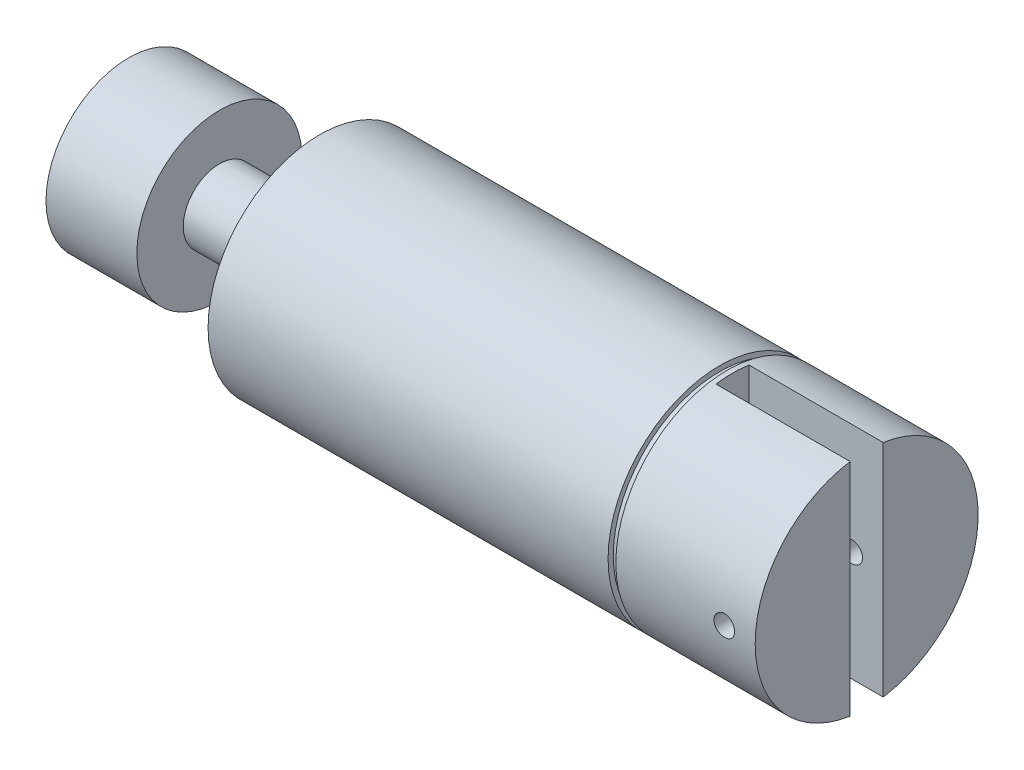
SolidWorks part; units mm, degrees
ref_plane "Front" through (0, 0, 0) normal (0, 0, 1) x (1, 0, 0)
ref_plane "Top" through (0, 0, 0) normal (0, 1, 0) x (1, 0, 0)
ref_plane "Right" through (0, 0, 0) normal (1, 0, 0) x (0, 0, -1)
sketch "Sketch1" plane through (0, 0, 0) normal (0, 0, 1) x (1, 0, 0)
  line L0 (-38.3901, 0) -> (38.3901, 0) construction
  line L1 (-57.25, 0) -> (-57.25, 8)
  line L2 (-57.25, 8) -> (-57.0422, 8)
  line L3 (-57.0422, 8) -> (-48.45, 8)
  line L4 (-48.45, 8) -> (-48.45, 5.8595)
  line L5 (-48.45, 3.5045) -> (-48.45, 5.8595)
  line L6 (-38.75, 3.5045) -> (-38.75, 10.8)
  line L7 (-48.45, 3.5045) -> (-38.75, 3.5045)
  line L8 (-38.75, 10.8) -> (-33.89, 10.8)
  line L9 (14.25, 10.8) -> (0.75, 10.8)
  line L10 (0.75, 10.8) -> (0.75, 10.3)
  line L11 (0.75, 10.3) -> (0, 10.3)
  line L12 (0, 10.3) -> (0, 10.8)
  line L14 (14.25, 10.8) -> (14.25, 0)
  line L15 (14.25, 0) -> (-57.25, 0)
  line L18 (-33.89, 10.8) -> (0, 10.8)
  dimension "D2" = 71.5
  dimension "D3" = 10.8
  dimension "D4" = 8.8
  dimension "D5" = 8
  dimension "D6" = 9.7
  dimension "D14" = 0.75
  dimension "D15" = 0.5
  dimension "D16" = 13.5
revolve "Revolve1" add sketch "Sketch1" angle 360 about L0
sketch "Sketch2" plane through (0, 0, 0) normal (0, 0, 1) x (1, 0, 0)
  line L0 (14.25, -10.8) -> (14.25, 10.8) construction
  circle A0 centre (11.25, 0) radius 1
  dimension "D1" = 2
  dimension "D2" = 3
extrude "Cut-Extrude1" cut sketch "Sketch2" against normal through all both and the other way through all
sketch "Sketch3" plane through (0, 0, 0) normal (0, 1, 0) x (1, 0, 0)
  line L0 (14.25, -10.8) -> (14.25, 10.8) construction
  line L1 (27.25, 1.6) -> (1.25, 1.6)
  line L2 (27.25, 1.6) -> (27.25, -1.6)
  line L3 (27.25, -1.6) -> (1.25, -1.6)
  line L4 (1.25, 1.6) -> (1.25, -1.6)
  line L5 (27.25, 1.6) -> (1.25, -1.6) construction
  line L6 (27.25, -1.6) -> (1.25, 1.6) construction
  line L7 (0.75, 10.3) -> (0.75, -10.3) construction
  point P0 (14.25, 0)
  dimension "D1" = 3.2
  dimension "D2" = 0.5
extrude "Cut-Extrude2" cut sketch "Sketch3" against normal through all both and the other way through all
